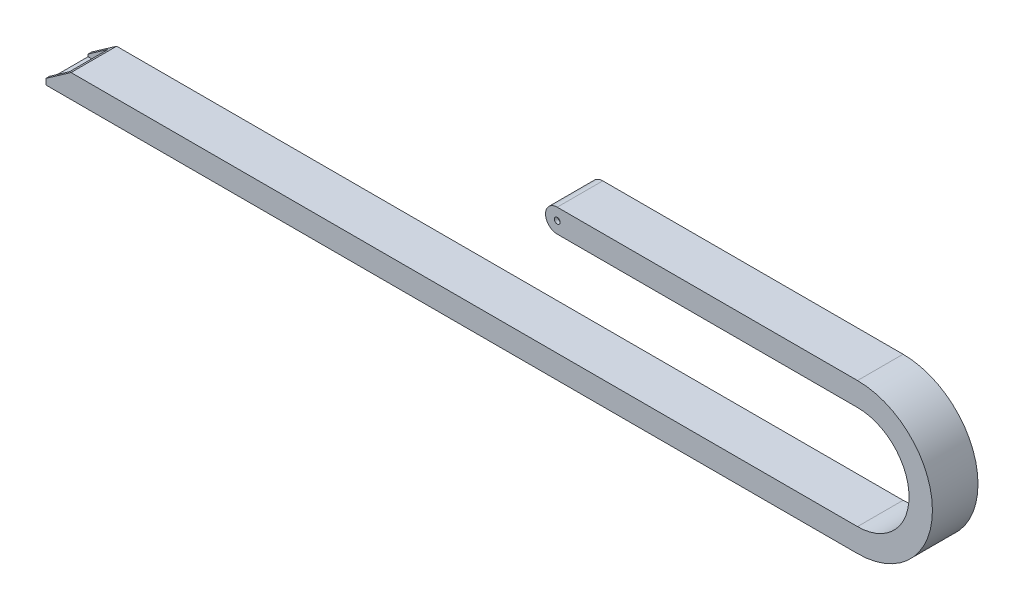
SolidWorks part; units mm, degrees
material "PA Type 6"
ref_plane "Front Plane" through (0, 0, 0) normal (0, 0, 1) x (1, 0, 0)
ref_plane "Top Plane" through (0, 0, 0) normal (0, 1, 0) x (1, 0, 0)
ref_plane "Right Plane" through (0, 0, 0) normal (1, 0, 0) x (0, 0, -1)
sketch "Sketch1" plane through (0, 0, 0) normal (0, 0, 1) x (1, 0, 0)
  line L6 (385.9625, -201.25) -> (-287.0362, -201.25)
  line L7 (-287.0362, -201.25) -> (-308.4584, -216.25)
  line L8 (-308.4584, -216.25) -> (-308.4584, -221.25)
  line L9 (-308.4584, -221.25) -> (385.9625, -221.25)
  line L10 (385.9625, -93) -> (129, -93)
  line L11 (129, -113) -> (385.9625, -113)
  line L12 (385.9625, -201.25) -> (-287.0362, -201.25)
  line L13 (-287.0362, -201.25) -> (-308.4584, -216.25)
  line L14 (-308.4584, -216.25) -> (-308.4584, -221.25)
  line L15 (-308.4584, -221.25) -> (385.9625, -221.25)
  line L16 (385.9625, -93) -> (129, -93)
  line L17 (129, -113) -> (385.9625, -113)
  arc A3 (385.9625, -221.25) -> (385.9625, -93) centre (385.9625, -157.125) ccw
  arc A4 (129, -93) -> (129, -113) centre (129, -103) ccw
  arc A5 (385.9625, -201.25) -> (385.9625, -113) centre (385.9625, -157.125) ccw
  arc A6 (385.9625, -221.25) -> (385.9625, -93) centre (385.9625, -157.125) ccw
  arc A7 (129, -93) -> (129, -113) centre (129, -103) ccw
  arc A8 (385.9625, -201.25) -> (385.9625, -113) centre (385.9625, -157.125) ccw
  dimension "D1" = 0
extrude "Boss-Extrude1" add sketch "Sketch1" along normal blind 39
shell "Shell1" thickness 3
ref_plane "Plane1" through (385.9625, 0, 0) normal (1, 0, 0) x (0, 0, -1)
sketch "Sketch2" plane through (385.9625, 0, 0) normal (-1, 0, 0) x (0, 0, 1)
  line L1 (36, -96) -> (3, -96)
  line L2 (36, -96) -> (36, -110)
  line L3 (36, -110) -> (3, -110)
  line L4 (3, -96) -> (3, -110)
  line L5 (36, -204.25) -> (3, -204.25)
  line L6 (36, -204.25) -> (36, -218.25)
  line L7 (36, -218.25) -> (3, -218.25)
  line L8 (3, -204.25) -> (3, -218.25)
extrude "Cut-Extrude1" cut sketch "Sketch2" along normal through all
sketch "Sketch3" plane through (0, 0, 39) normal (0, 0, 1) x (1, 0, 0)
  circle A0 centre (129, -103) radius 2.5
  dimension "D1" = 5
extrude "Cut-Extrude2" cut sketch "Sketch3" against normal through all
